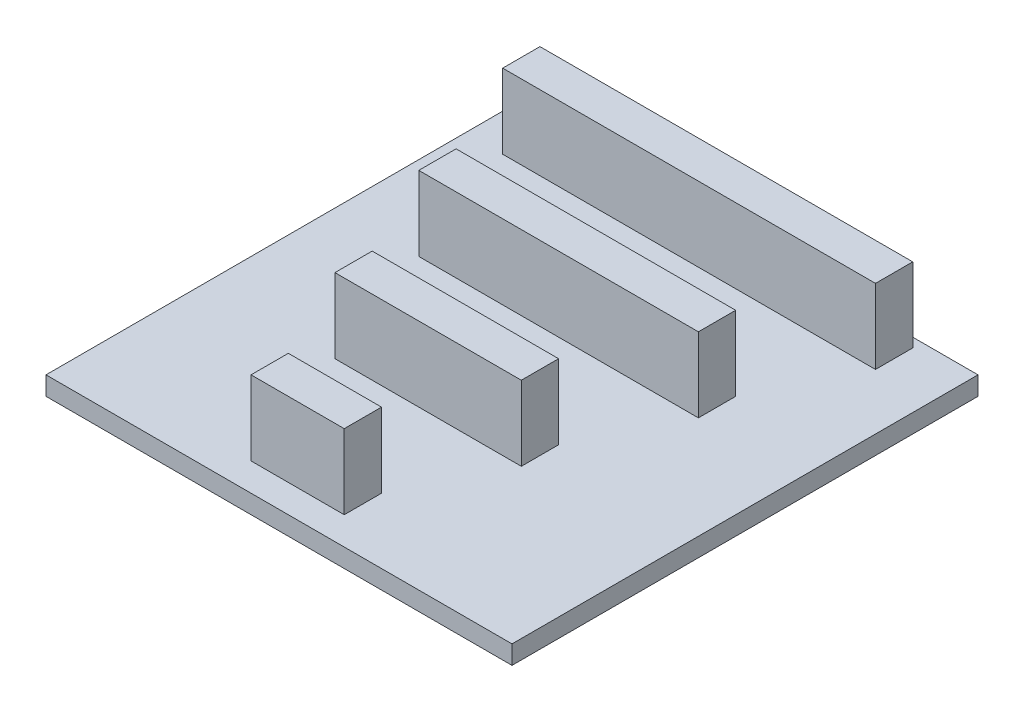
SolidWorks part; units mm, degrees
ref_plane "Front Plane" through (0, 0, 0) normal (0, 0, 1) x (1, 0, 0)
ref_plane "Top Plane" through (0, 0, 0) normal (0, 1, 0) x (1, 0, 0)
ref_plane "Right Plane" through (0, 0, 0) normal (1, 0, 0) x (0, 0, -1)
ref_plane "Plane1" through (0, 1, 0) normal (0, 1, 0) x (1, 0, 0)
sketch "Sketch1" plane through (0, 0, 0) normal (0, 1, 0) x (1, 0, 0)
  line L1 (25, -25) -> (-25, -25)
  line L2 (25, -25) -> (25, 25)
  line L3 (25, 25) -> (-25, 25)
  line L4 (-25, -25) -> (-25, 25)
  line L5 (25, -25) -> (-25, 25) construction
  line L6 (25, 25) -> (-25, -25) construction
  point P0 (0, 0)
  dimension "D1" = 50
  dimension "D2" = 50
sketch "Sketch5" plane through (0, 1, 0) normal (0, 1, 0) x (1, 0, 0)
  line L0 (-25, -25) -> (-25, 25) construction
  line L1 (-5, -19) -> (5, -19)
  line L2 (-5, -19) -> (-5, -23)
  line L3 (-5, -23) -> (5, -23)
  line L4 (5, -19) -> (5, -23)
  line L5 (-10, -5) -> (10, -5)
  line L6 (-10, -5) -> (-10, -9)
  line L7 (-10, -9) -> (10, -9)
  line L8 (10, -5) -> (10, -9)
  line L9 (-15, 9) -> (15, 9)
  line L10 (-15, 9) -> (-15, 5)
  line L11 (-15, 5) -> (15, 5)
  line L12 (15, 9) -> (15, 5)
  line L13 (-20, 23) -> (20, 23)
  line L14 (-20, 23) -> (-20, 19)
  line L15 (-20, 19) -> (20, 19)
  line L16 (20, 23) -> (20, 19)
  line L17 (25, -25) -> (-25, -25) construction
  dimension "D1" = 4
  dimension "D2" = 4
  dimension "D3" = 4
  dimension "D4" = 4
  dimension "D5" = 10
  dimension "D6" = 20
  dimension "D7" = 30
  dimension "D8" = 40
  dimension "D9" = 5
  dimension "D10" = 10
  dimension "D11" = 15
  dimension "D12" = 20
  dimension "D13" = 2
  dimension "D14" = 10
  dimension "D15" = 10
  dimension "D16" = 10
extrude "Boss-Extrude4" add sketch "Sketch5" along normal blind 8
extrude "Boss-Extrude5" add sketch "Sketch1" against normal blind 2 separate body
